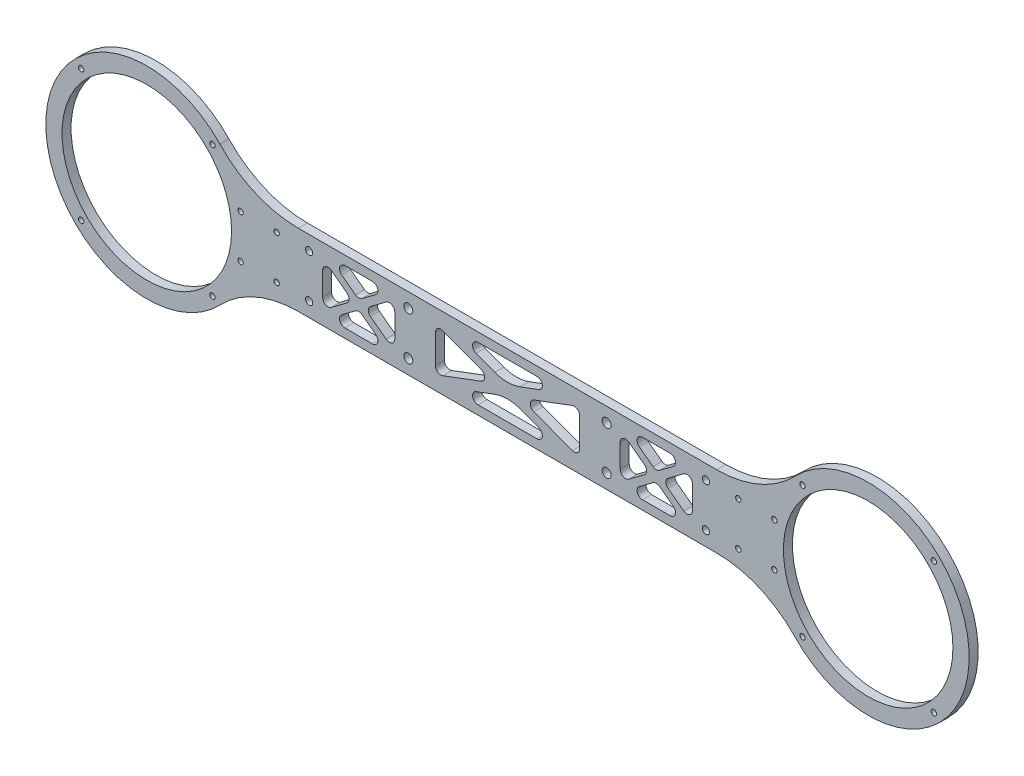
SolidWorks part; units mm, degrees
material "7075-T6，板材(SS)"
ref_plane "前视基准面" through (0, 0, 0) normal (0, 0, 1) x (1, 0, 0)
ref_plane "上视基准面" through (0, 0, 0) normal (0, 1, 0) x (1, 0, 0)
ref_plane "右视基准面" through (0, 0, 0) normal (1, 0, 0) x (0, 0, -1)
sketch "草图1" plane through (0, 0, 0) normal (0, 0, 1) x (1, 0, 0)
  line L0 (0, 0) -> (400, 0) construction
  line L3 (347.6932, 20) -> (52.3068, 20)
  line L5 (347.6932, -20) -> (52.3068, -20)
  circle A0 centre (0, 0) radius 47
  arc A1 (52.3068, 20) -> (52.3068, -20) centre (0, 0) ccw
  circle A2 centre (400, 0) radius 47
  arc A3 (347.6932, -20) -> (347.6932, 20) centre (400, 0) ccw
  dimension "D1" = 56
  dimension "D2" = 56
  dimension "D3" = 400
  dimension "D4" = 40
  dimension "D5" = 20
extrude "凸台-拉伸1" add sketch "草图1" along normal blind 5
fillet "圆角1" radius 60 4 edges at (52.3068, 20, 2.5) (52.3068, -20, 2.5) (347.6932, -20, 2.5) (347.6932, 20, 2.5)
sketch "草图31" plane through (0, 0, 5) normal (0, 0, 1) x (1, 0, 0)
  line L0 (0, 0) -> (36.416, 36.416) construction
  line L1 (400, 0) -> (436.416, 36.416) construction
  line L2 (400, 0) -> (400, 51.5) construction
  circle A0 centre (0, 0) radius 51.5 construction
  circle A1 centre (36.416, 36.416) radius 1.5
  circle A2 centre (36.416, -36.416) radius 1.5
  circle A3 centre (-36.416, -36.416) radius 1.5
  circle A4 centre (-36.416, 36.416) radius 1.5
  circle A5 centre (400, 0) radius 51.5 construction
  circle A6 centre (436.416, 36.416) radius 1.5
  circle A7 centre (436.416, -36.416) radius 1.5
  circle A8 centre (363.584, -36.416) radius 1.5
  circle A9 centre (363.584, 36.416) radius 1.5
  point P14 (0, 0)
  point P26 (400, 0)
  dimension "D1" = 4
  dimension "D2" = 4
  dimension "D3" = 45
extrude "切除-拉伸14" cut sketch "草图31" against normal blind 5
sketch "草图35" plane through (0, 0, 5) normal (0, 0, 1) x (1, 0, 0)
  line L0 (200, 20) -> (200, -20) construction
  line L1 (316, 20) -> (84, 20) construction
  line L2 (84, -20) -> (316, -20) construction
  line L4 (145, -12) -> (255, -12) construction
  line L5 (145, -12) -> (145, 12) construction
  line L6 (145, 12) -> (255, 12) construction
  line L7 (255, -12) -> (255, 12) construction
  line L8 (145, -12) -> (255, 12) construction
  line L9 (145, 12) -> (255, -12) construction
  circle A0 centre (145, 12) radius 2.5
  circle A1 centre (255, 12) radius 2.5
  circle A2 centre (145, -12) radius 2.5
  circle A3 centre (255, -12) radius 2.5
  circle A8 centre (90, -12) radius 2
  circle A9 centre (90, 12) radius 2
  circle A14 centre (310, -12) radius 2
  circle A15 centre (310, 12) radius 2
  point P4 (200, 0)
  dimension "D3" = 5
  dimension "D4" = 5
  dimension "D5" = 5
  dimension "D6" = 5
  dimension "D1" = 24
  dimension "D2" = 110
extrude "切除-拉伸17" cut sketch "草图35" against normal blind 10
sketch "草图37" plane through (0, 0, 0) normal (0, 0, -1) x (-1, 0, 0)
  line L0 (-200, 20) -> (-200, -20) construction
  line L1 (-316, 20) -> (-84, 20) construction
  line L2 (-84, -20) -> (-316, -20) construction
  line L3 (-240.8778, -12.6592) -> (-160.8778, 17.3408)
  line L4 (-240, -15) -> (-160, -15)
  line L5 (-240, -15) -> (-240, 15)
  line L6 (-240, 15) -> (-160, 15)
  line L7 (-160, -15) -> (-160, 15)
  line L8 (-240, -15) -> (-160, 15) construction
  line L9 (-240, 15) -> (-160, -15) construction
  line L10 (-239.1222, -17.3408) -> (-159.1222, 12.6592)
  line L11 (-240.8778, 12.6592) -> (-160.8778, -17.3408)
  line L12 (-239.1222, 17.3408) -> (-159.1222, -12.6592)
  point P6 (-200, 0)
  dimension "D1" = 30
  dimension "D2" = 80
  dimension "D3" = 2.5
  dimension "D4" = 2.5
  dimension "D5" = 2.5
  dimension "D6" = 2.5
extrude "切除-拉伸18" cut sketch "草图37" against normal blind 10 contours L6 L12 L3 | L10 L12 L7 | L11 L10 L4 | L11 L5 L3
fillet "圆角2" radius 3 10 edges at (232.88, -15, 2.5) (167.12, -15, 2.5) (192.88, 0, 2.5) (240, -12.33, 2.5) (240, 12.33, 2.5) (207.12, 0, 2.5) (160, -12.33, 2.5) (160, 12.33, 2.5) (167.12, 15, 2.5) (232.88, 15, 2.5)
fillet "圆角3" radius 20 2 edges at (200, -2.67, 2.5) (200, 2.67, 2.5)
sketch "草图38" plane through (0, 0, 0) normal (0, 0, -1) x (-1, 0, 0)
  line L0 (-310, 12) -> (-255, 12) construction
  line L1 (-282.5, 12) -> (-282.5, 0) construction
  line L2 (-303.7, -13.4) -> (-263.7, 16.6)
  line L3 (-302.5, -15) -> (-262.5, -15)
  line L4 (-302.5, -15) -> (-302.5, 15)
  line L5 (-302.5, 15) -> (-262.5, 15)
  line L6 (-262.5, -15) -> (-262.5, 15)
  line L7 (-302.5, -15) -> (-262.5, 15) construction
  line L8 (-302.5, 15) -> (-262.5, -15) construction
  line L9 (-301.3, -16.6) -> (-261.3, 13.4)
  line L10 (-303.7, 13.4) -> (-263.7, -16.6)
  line L11 (-301.3, 16.6) -> (-261.3, -13.4)
  line L12 (-200, 20) -> (-200, -20) construction
  line L13 (-316, 20) -> (-84, 20) construction
  line L14 (-84, -20) -> (-316, -20) construction
  line L15 (-97.5, 15) -> (-137.5, -15) construction
  line L16 (-97.5, -15) -> (-137.5, 15) construction
  line L17 (-117.5, 12) -> (-117.5, 0) construction
  line L18 (-90, 12) -> (-145, 12) construction
  line L19 (-98.7, 16.6) -> (-138.7, -13.4)
  line L20 (-96.3, 13.4) -> (-136.3, -16.6)
  line L21 (-98.7, -16.6) -> (-138.7, 13.4)
  line L22 (-137.5, -15) -> (-137.5, 15)
  line L23 (-97.5, 15) -> (-137.5, 15)
  line L24 (-97.5, -15) -> (-97.5, 15)
  line L25 (-97.5, -15) -> (-137.5, -15)
  line L26 (-96.3, -13.4) -> (-136.3, 16.6)
  dimension "D1" = 12
  dimension "D2" = 30
  dimension "D3" = 40
  dimension "D4" = 2
  dimension "D5" = 2
  dimension "D6" = 2
  dimension "D7" = 2
extrude "切除-拉伸19" cut sketch "草图38" against normal blind 10 contours L10 L4 L2 | L9 L11 L6 | L10 L9 L3 | L5 L11 L2 | L25 L21 L20 | L26 L24 L20 | L26 L19 L23 | L22 L19 L21
sketch "草图39" plane through (0, 0, 5) normal (0, 0, 1) x (1, 0, 0)
  circle A0 centre (72.002, -12) radius 1.5 construction
  circle A1 centre (52, -12) radius 1.5 construction
  circle A2 centre (72.002, 12) radius 1.5 construction
  circle A3 centre (52, 12) radius 1.5 construction
  circle A4 centre (72.002, -12) radius 1.5
  circle A5 centre (52, -12) radius 1.5
  circle A6 centre (72.002, 12) radius 1.5
  circle A7 centre (52, 12) radius 1.5
  circle A8 centre (348, 12) radius 1.5 construction
  circle A9 centre (348, 12) radius 1.5
  circle A10 centre (327.998, 12) radius 1.5 construction
  circle A11 centre (327.998, -12) radius 1.5 construction
  circle A12 centre (348, -12) radius 1.5 construction
  circle A13 centre (327.998, 12) radius 1.5
  circle A14 centre (327.998, -12) radius 1.5
  circle A15 centre (348, -12) radius 1.5
extrude "切除-拉伸20" cut sketch "草图39" against normal blind 10
fillet "圆角4" radius 3 24 edges at (117.5, -2.5, 2.5) (100.8333, -15, 2.5) (134.1667, -15, 2.5) (282.5, 2.5, 2.5) (299.1667, 15, 2.5) (265.8333, 15, 2.5) (262.5, -12.5, 2.5) (279.1667, 0, 2.5) (262.5, 12.5, 2.5) (299.1667, -15, 2.5) (282.5, -2.5, 2.5) (265.8333, -15, 2.5) (120.8333, 0, 2.5) (137.5, -12.5, 2.5) (137.5, 12.5, 2.5) (97.5, 12.5, 2.5) (97.5, -12.5, 2.5) (114.1667, 0, 2.5) (100.8333, 15, 2.5) (117.5, 2.5, 2.5) (134.1667, 15, 2.5) (285.8333, 0, 2.5) (302.5, -12.5, 2.5) (302.5, 12.5, 2.5)
equation "\"www\"=252"
